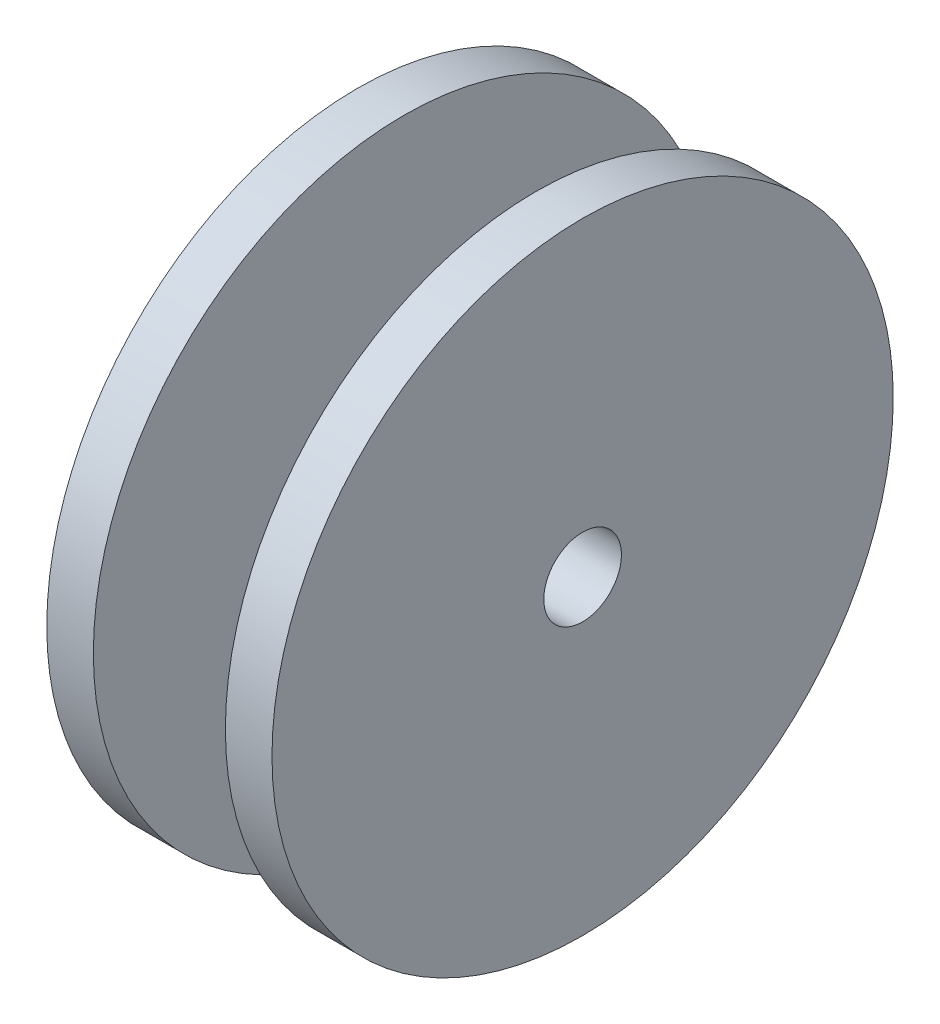
SolidWorks part; units mm, degrees
ref_plane "Front Plane" through (0, 0, 0) normal (0, 0, 1) x (1, 0, 0)
ref_plane "Top Plane" through (0, 0, 0) normal (0, 1, 0) x (1, 0, 0)
ref_plane "Right Plane" through (0, 0, 0) normal (1, 0, 0) x (0, 0, -1)
sketch "Sketch1" plane through (0, 0, 0) normal (1, 0, 0) x (0, 0, -1)
  circle A0 centre (0, 0) radius 20
  dimension "D1" = 40
extrude "Boss-Extrude1" add sketch "Sketch1" along normal mid plane 14.5
sketch "Sketch2" plane through (0, 0, 0) normal (1, 0, 0) x (0, 0, -1)
  circle A0 centre (0, 0) radius 7.5
  circle A1 centre (0, 0) radius 20
  circle A4 centre (0, 0) radius 20 construction
  dimension "D1" = 15
extrude "Cut-Extrude1" cut sketch "Sketch2" against normal mid plane 8.5
sketch "Sketch3" plane through (7.25, 0, 0) normal (1, 0, 0) x (0, 0, -1)
  circle A0 centre (0, 0) radius 2.5
  dimension "D1" = 5
extrude "Cut-Extrude2" cut sketch "Sketch3" against normal through all both and the other way through all
